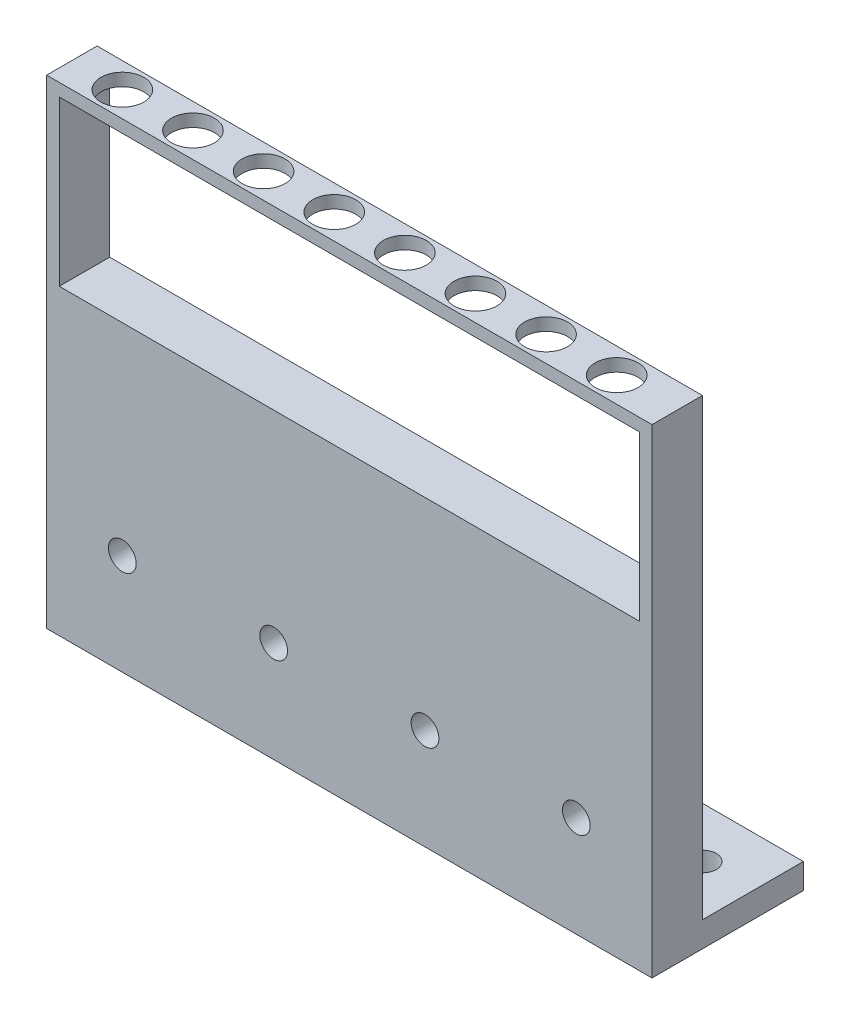
SolidWorks part; units mm, degrees
ref_plane "Front Plane" through (0, 0, 0) normal (0, 0, 1) x (1, 0, 0)
ref_plane "Top Plane" through (0, 0, 0) normal (0, 1, 0) x (1, 0, 0)
ref_plane "Right Plane" through (0, 0, 0) normal (1, 0, 0) x (0, 0, -1)
sketch "Sketch1" plane through (0, 0, 0) normal (0, 1, 0) x (1, 0, 0)
  line L1 (-76.2, -6.35) -> (76.2, -6.35)
  line L2 (-76.2, -6.35) -> (-76.2, 6.35)
  line L3 (-76.2, 6.35) -> (76.2, 6.35)
  line L4 (76.2, -6.35) -> (76.2, 6.35)
  line L5 (-76.2, -6.35) -> (76.2, 6.35) construction
  line L6 (-76.2, 6.35) -> (76.2, -6.35) construction
  point P0 (0, 0)
  dimension "D1" = 12.7
  dimension "D2" = 152.4
extrude "Boss-Extrude1" add sketch "Sketch1" along normal blind 76.2
sketch "Sketch2" plane through (0, 0, 0) normal (0, 1, 0) x (1, 0, 0)
  line L0 (-76.2, 6.35) -> (-76.2, -6.35) construction
  line L1 (-76.2, 19.05) -> (-76.2, 6.35)
  line L2 (-76.2, 6.35) -> (76.2, 6.35)
  line L3 (76.2, 31.75) -> (-76.2, 31.75)
  line L4 (-76.2, 19.05) -> (-76.2, 31.75)
  line L5 (0, 0) -> (-76.2, 31.75) construction
  line L6 (76.2, 31.75) -> (0, 0) construction
  line L7 (76.2, 6.35) -> (-76.2, 6.35) construction
  line L8 (-23.5905, 31.75) -> (-23.5905, 6.35) construction
  line L9 (-23.5905, 19.05) -> (-76.2, 19.05) construction
  line L10 (76.2, 6.35) -> (76.2, 31.75)
  circle A0 centre (-63.5, 19.05) radius 3.4925
  circle A1 centre (-38.1, 19.05) radius 3.4925
  circle A2 centre (-12.7, 19.05) radius 3.4925
  circle A3 centre (12.7, 19.05) radius 3.4925
  circle A4 centre (38.1, 19.05) radius 3.4925
  circle A5 centre (63.5, 19.05) radius 3.4925
  point P0 (0, 0)
  dimension "D2" = 6.985
  dimension "D1" = 25.4
  dimension "D3" = 6
  dimension "D4" = 12.7
extrude "Boss-Extrude4" add sketch "Sketch2" along normal blind 6.35
sketch "Sketch3" plane through (0, 0, 6.35) normal (0, 0, 1) x (1, 0, 0)
  line L0 (-76.2, 76.2) -> (-76.2, 120.65)
  line L1 (-76.2, 120.65) -> (76.2, 120.65)
  line L2 (76.2, 120.65) -> (76.2, 76.2)
  line L3 (76.2, 76.2) -> (76.2, 0) construction
  line L4 (-76.2, 76.2) -> (-76.2, 0) construction
  line L5 (76.2, 76.2) -> (73.025, 76.2)
  line L6 (-76.2, 76.2) -> (76.2, 76.2) construction
  line L7 (73.025, 76.2) -> (73.025, 117.475)
  line L8 (73.025, 117.475) -> (-73.025, 117.475)
  line L9 (-73.025, 117.475) -> (-73.025, 76.2)
  line L10 (-73.025, 76.2) -> (-76.2, 76.2)
  line L11 (-73.025, 117.475) -> (-73.025, 120.65) construction
  dimension "D1" = 3.175
  dimension "D2" = 44.45
extrude "Boss-Extrude5" add sketch "Sketch3" against normal up to surface (12.7 mm away) up to face at (0, 41.275, -6.35)
sketch "Sketch4" plane through (0, 120.65, 0) normal (0, 1, 0) x (1, 0, 0)
  line L0 (-76.2, 6.35) -> (-76.2, -6.35) construction
  circle A0 centre (-63.5, 0) radius 5.3975
  circle A1 centre (-45.72, 0) radius 5.3975
  circle A2 centre (-27.94, 0) radius 5.3975
  circle A3 centre (-10.16, 0) radius 5.3975
  circle A4 centre (7.62, 0) radius 5.3975
  circle A5 centre (25.4, 0) radius 5.3975
  circle A6 centre (43.18, 0) radius 5.3975
  circle A7 centre (60.96, 0) radius 5.3975
  dimension "D1" = 10.795
  dimension "D2" = 12.7
  dimension "D3" = 8
extrude "Cut-Extrude1" cut sketch "Sketch4" against normal up to next
sketch "Sketch5" plane through (0, 0, -6.35) normal (0, 0, -1) x (-1, 0, 0)
  line L0 (-76.2, 0) -> (76.2, 0) construction
  line L1 (-76.2, 6.35) -> (-76.2, 0) construction
  circle A0 centre (-57.15, 25.4) radius 3.4925
  circle A1 centre (-19.05, 25.4) radius 3.4925
  circle A2 centre (19.05, 25.4) radius 3.4925
  circle A3 centre (57.15, 25.4) radius 3.4925
  dimension "D2" = 6.985
  dimension "D1" = 25.4
  dimension "D3" = 19.05
  dimension "D4" = 4
extrude "Cut-Extrude2" cut sketch "Sketch5" against normal through all
